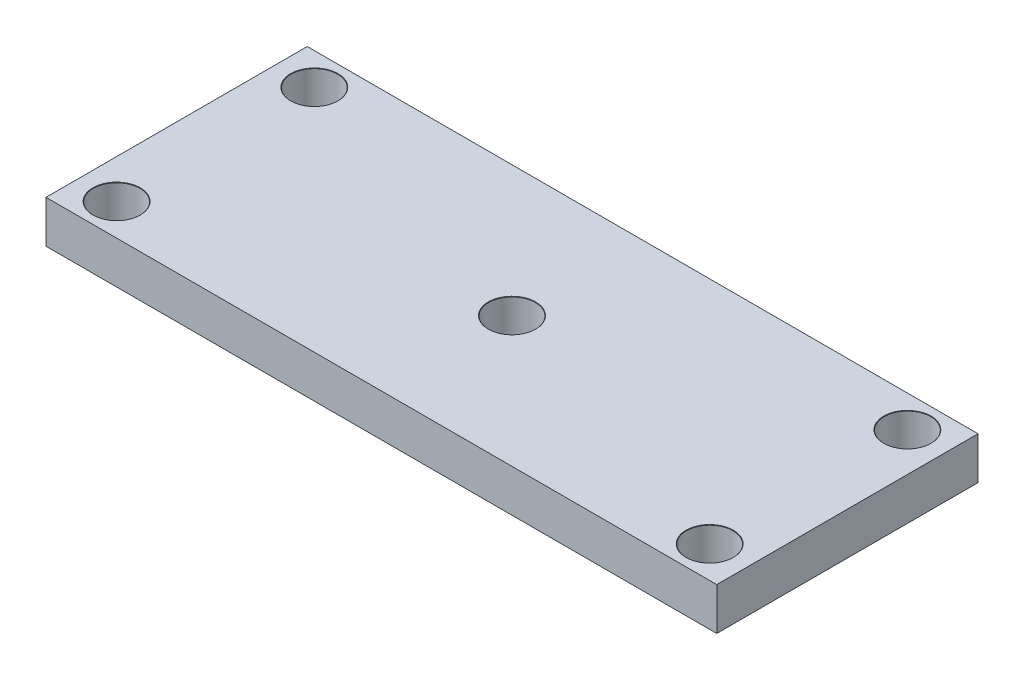
SolidWorks part; units mm, degrees
ref_plane "Front Plane" through (0, 0, 0) normal (0, 0, 1) x (1, 0, 0)
ref_plane "Top Plane" through (0, 0, 0) normal (0, 1, 0) x (1, 0, 0)
ref_plane "Right Plane" through (0, 0, 0) normal (1, 0, 0) x (0, 0, -1)
sketch "Sketch1" plane through (0, 0, 0) normal (0, 1, 0) x (1, 0, 0)
  line L1 (-23.75, 9.25) -> (23.75, 9.25)
  line L2 (-23.75, 9.25) -> (-23.75, -9.25)
  line L3 (-23.75, -9.25) -> (23.75, -9.25)
  line L4 (23.75, 9.25) -> (23.75, -9.25)
  line L5 (-23.75, 9.25) -> (23.75, -9.25) construction
  line L6 (-23.75, -9.25) -> (23.75, 9.25) construction
  point P0 (0, 0)
  dimension "D1" = 47.5
  dimension "D2" = 18.5
extrude "Boss-Extrude1" add sketch "Sketch1" along normal blind 3
hole_wizard "Ø3.3 (3.3) Diameter Hole1" positions "Sketch2" profile "Sketch3" hole size "Ø3.3" standard "ISO" end condition through all
sketch "Sketch2" plane through (0, 3, 0) normal (0, 1, 0) x (1, 0, 0)
  line L1 (-21, 7) -> (21, 7)
  line L2 (-21, 7) -> (-21, -7)
  line L3 (-21, -7) -> (21, -7)
  line L4 (21, 7) -> (21, -7)
  line L5 (-21, 7) -> (21, -7) construction
  line L6 (-21, -7) -> (21, 7) construction
  point P1 (0, 0)
  point P2 (21, -7)
  point P33 (-21, 7)
  point P34 (-21, -7)
  point P35 (21, 7)
  dimension "D1" = 42
  dimension "D2" = 14
sketch "Sketch3" plane through (0, 3, 0) normal (1, 0, 0) x (0, 0, 1)
  line L0 (0, 0) -> (0, 3)
  line L1 (0, 3) -> (1.65, 3)
  line L2 (1.65, 3) -> (1.65, 0.025)
  line L3 (1.65, 0.025) -> (1.675, 0)
  line L5 (1.675, 0) -> (0, 0)
  line L6 (-1.65, 0.025) -> (-1.675, 0) construction
  line L11 (0, -6.35) -> (0, 107.95) construction
  dimension "Thru Hole Dia." = 3.3
  dimension "Thru Hole Depth" = 3
  dimension "Near C'Sink Dia." = 3.35
  dimension "Near C'Sink Angle" = 90
